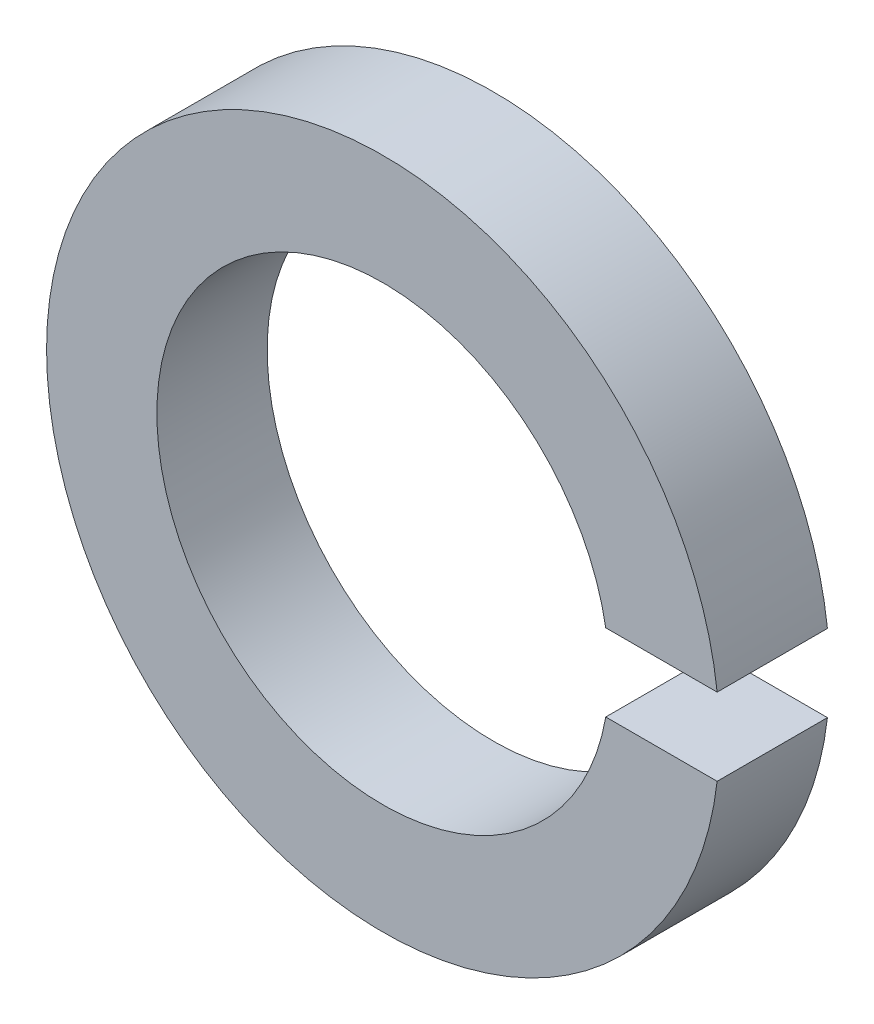
SolidWorks part; units mm, degrees
ref_plane "Спереди" through (0, 0, 0) normal (0, 0, 1) x (1, 0, 0)
ref_plane "Сверху" through (0, 0, 0) normal (0, 1, 0) x (1, 0, 0)
ref_plane "Справа" through (0, 0, 0) normal (1, 0, 0) x (0, 0, -1)
sketch "Эскиз1" plane through (0, 0, 0) normal (0, 0, 1) x (1, 0, 0)
  circle A0 centre (0, 0) radius 3.05
  circle A1 centre (0, 0) radius 2.05
  dimension "D1" = 6.1
  dimension "D2" = 4.1
extrude "Вытянуть1" add sketch "Эскиз1" along normal blind 1
sketch "Эскиз2" plane through (0, 0, 1) normal (0, 0, 1) x (1, 0, 0)
  line L0 (0, 0) -> (0.123, 0) construction
  line L1 (3.05, 0) -> (-3.05, 0) construction
  line L3 (1.9972, 0.35) -> (3.1092, 0.35)
  line L4 (1.9972, 0.35) -> (1.9972, -0.35)
  line L5 (1.9972, -0.35) -> (3.1092, -0.35)
  line L6 (3.1092, 0.35) -> (3.1092, -0.35)
  circle A0 centre (0, 0) radius 3.05 construction
  dimension "D1" = 0.35
  dimension "D2" = 0.7
extrude "Вырез-Вытянуть1" cut sketch "Эскиз2" against normal through all
